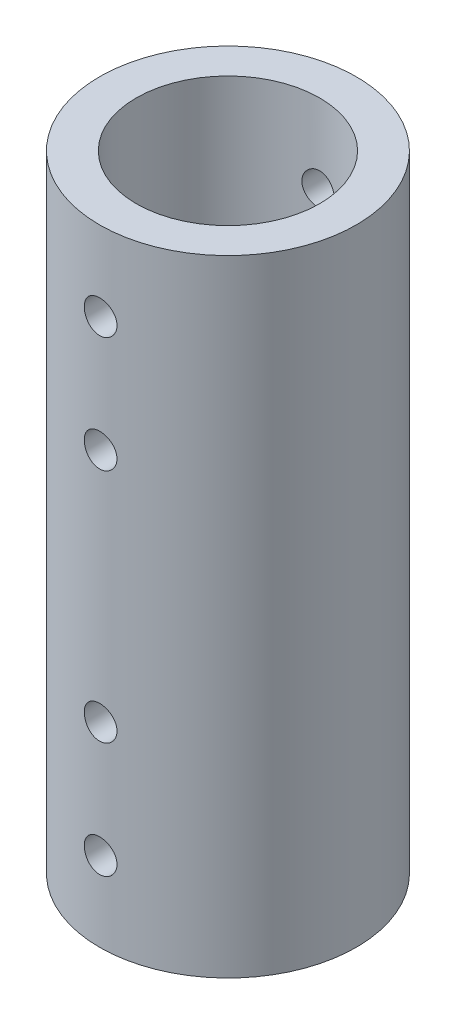
SolidWorks part; units mm, degrees
material "PVC Rigid"
ref_plane "Front Plane" through (0, 0, 0) normal (0, 0, 1) x (1, 0, 0)
ref_plane "Top Plane" through (0, 0, 0) normal (0, 1, 0) x (1, 0, 0)
ref_plane "Right Plane" through (0, 0, 0) normal (1, 0, 0) x (0, 0, -1)
sketch "Sketch1" plane through (0, 0, 0) normal (0, 1, 0) x (1, 0, 0)
  circle A0 centre (0, 0) radius 13.335
  circle A1 centre (0, 0) radius 9.525
  dimension "D1" = 26.67
  dimension "D2" = 19.05
extrude "Boss-Extrude1" add sketch "Sketch1" along normal blind 65
sketch "Sketch4" plane through (0, 0, 0) normal (0, 0, 1) x (1, 0, 0)
  line L0 (0, 65) -> (0, 44.7442) construction
  line L1 (9.525, 65) -> (-9.525, 65) construction
  line L2 (13.335, 65) -> (-13.335, 65) construction
  circle A0 centre (0, 56.7442) radius 1.7
  circle A1 centre (0, 44.7442) radius 1.7
  circle A3 centre (0, 44.7442) radius 1.7 construction
  dimension "D1" = 3.4
  dimension "D2" = 3.4
  dimension "D3" = 8.2558
  dimension "D4" = 12
extrude "Cut-Extrude1" cut sketch "Sketch4" against normal through all both and the other way through all
sketch "Sketch6" plane through (0, 0, 0) normal (0, 0, 1) x (1, 0, 0)
  line L0 (13.335, 65) -> (13.335, 0) construction
  line L1 (13.335, 65) -> (-13.335, 65) construction
  line L2 (-13.335, 0) -> (13.335, 0) construction
  line L3 (13.335, 32.5) -> (-13.335, 32.5) construction
  line L4 (-13.335, 65) -> (-13.335, 0) construction
  line L5 (13.335, 0) -> (13.335, 65) construction
ref_plane "Plane2" through (0, 32.5, 0) normal (0, 1, 0) x (1, 0, 0)
mirror "Mirror2" about plane through (0, 32.5, 0) normal (0, 1, 0) of "Cut-Extrude1"
